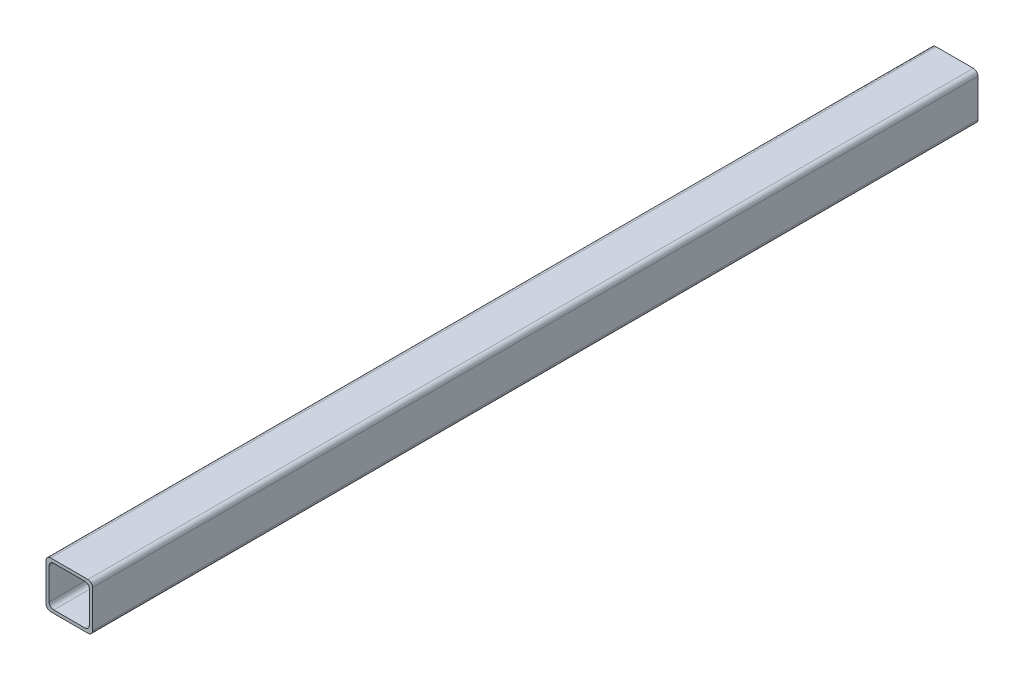
SolidWorks part; units mm, degrees
ref_plane "Plan de face" through (0, 0, 0) normal (0, 0, 1) x (1, 0, 0)
ref_plane "Plan de dessus" through (0, 0, 0) normal (0, 1, 0) x (1, 0, 0)
ref_plane "Plan de droite" through (0, 0, 0) normal (1, 0, 0) x (0, 0, -1)
sketch "Esquisse1" plane through (0, 0, 0) normal (0, 0, 1) x (1, 0, 0)
  line L1 (-12, -15) -> (12, -15)
  line L2 (-15, -12) -> (-15, 12)
  line L3 (-12, 15) -> (12, 15)
  line L4 (15, -12) -> (15, 12)
  line L5 (0, 15) -> (0, -15) construction
  line L6 (-15, 0) -> (15, 0) construction
  line L7 (-10, -13) -> (10, -13)
  line L8 (-13, -10) -> (-13, 10)
  line L9 (-10, 13) -> (10, 13)
  line L10 (13, -10) -> (13, 10)
  line L11 (0, 13) -> (0, -13) construction
  line L12 (-13, 0) -> (13, 0) construction
  arc A0 (10, -13) -> (13, -10) centre (10, -10) ccw
  arc A1 (12, -15) -> (15, -12) centre (12, -12) ccw
  arc A2 (-13, 10) -> (-10, 13) centre (-10, 10) cw
  arc A3 (-10, -13) -> (-13, -10) centre (-10, -10) cw
  arc A4 (10, 13) -> (13, 10) centre (10, 10) cw
  arc A5 (-15, 12) -> (-12, 15) centre (-12, 12) cw
  arc A6 (-12, -15) -> (-15, -12) centre (-12, -12) cw
  arc A7 (12, 15) -> (15, 12) centre (12, 12) cw
  point P0 (0, 0)
  point P4 (0, 0)
  point P18 (15, -15)
  point P27 (-15, 15)
  point P32 (15, 15)
  dimension "D5" = 3
  dimension "D1" = 30
  dimension "D2" = 30
  dimension "D3" = 26
  dimension "D4" = 26
extrude "Boss.-Extru.1" add sketch "Esquisse1" against normal blind 570
